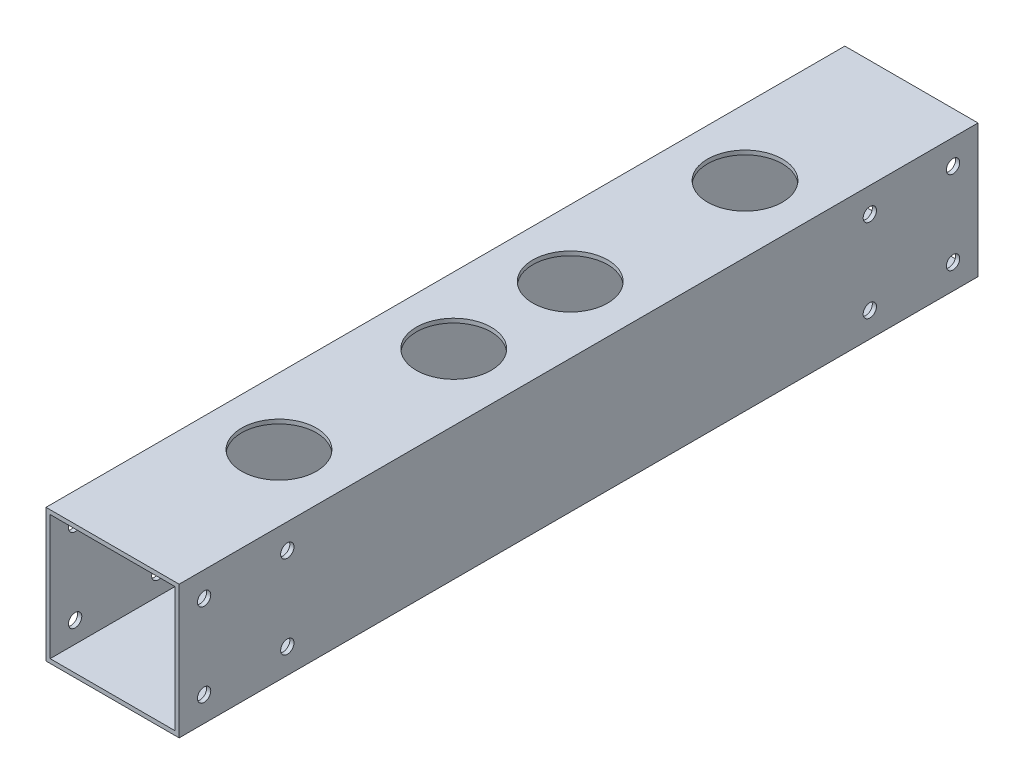
SolidWorks part; units mm, degrees
material "1060 Alloy"
ref_plane "Front Plane" through (0, 0, 0) normal (0, 0, 1) x (1, 0, 0)
ref_plane "Top Plane" through (0, 0, 0) normal (0, 1, 0) x (1, 0, 0)
ref_plane "Right Plane" through (0, 0, 0) normal (1, 0, 0) x (0, 0, -1)
sketch "Sketch2" plane through (0, 0, 0) normal (0, 0, 1) x (1, 0, 0)
  line L1 (0, 0) -> (50.8, 0)
  line L2 (0, 0) -> (0, 50.8)
  line L3 (0, 50.8) -> (50.8, 50.8)
  line L4 (50.8, 0) -> (50.8, 50.8)
  line L5 (1.5875, 1.5875) -> (49.2125, 1.5875)
  line L6 (1.5875, 1.5875) -> (1.5875, 49.2125)
  line L7 (1.5875, 49.2125) -> (49.2125, 49.2125)
  line L8 (49.2125, 1.5875) -> (49.2125, 49.2125)
  dimension "D1" = 50.8
  dimension "D2" = 50.8
  dimension "D3" = 1.5875
  dimension "D4" = 1.5875
  dimension "D5" = 1.5875
  dimension "D6" = 1.5875
extrude "Boss-Extrude1" add sketch "Sketch2" along normal blind 304.8
sketch "Sketch3" plane through (0, 50.8, 0) normal (0, 1, 0) x (1, 0, 0)
  line L0 (0, -152.4) -> (50.8, -152.4) construction
  line L1 (0, -304.8) -> (0, 0) construction
  line L2 (50.8, -304.8) -> (50.8, 0) construction
  circle A0 centre (25.4, -241.3) radius 14.2875
  circle A3 centre (25.4, -174.625) radius 14.2875
  circle A4 centre (25.4, -130.175) radius 14.2875
  circle A5 centre (25.4, -63.5) radius 14.2875
  dimension "D1" = 28.575
  dimension "D2" = 25.4
  dimension "D3" = 88.9
  dimension "D4" = 22.225
extrude "Cut-Extrude1" cut sketch "Sketch3" against normal through all
sketch "Sketch4" plane through (0, 0, 0) normal (-1, 0, 0) x (0, 0, 1)
  line L0 (152.4, 50.8) -> (152.4, 0) construction
  line L1 (304.8, 50.8) -> (0, 50.8) construction
  line L2 (304.8, 0) -> (0, 0) construction
  line L3 (50.8, 50.8) -> (50.8, 0) construction
  line L4 (0, 50.8) -> (0, 0) construction
  circle A0 centre (9.525, 41.275) radius 2.54
  circle A1 centre (9.525, 9.525) radius 2.54
  circle A2 centre (41.275, 41.275) radius 2.54
  circle A3 centre (41.275, 9.525) radius 2.54
  circle A4 centre (263.525, 9.525) radius 2.54
  circle A5 centre (263.525, 41.275) radius 2.54
  circle A6 centre (295.275, 9.525) radius 2.54
  circle A7 centre (295.275, 41.275) radius 2.54
  dimension "D2" = 5.08
  dimension "D1" = 50.8
  dimension "D3" = 9.525
  dimension "D4" = 9.525
  dimension "D5" = 9.525
  dimension "D6" = 9.525
extrude "Cut-Extrude2" cut sketch "Sketch4" against normal through all both and the other way through all
